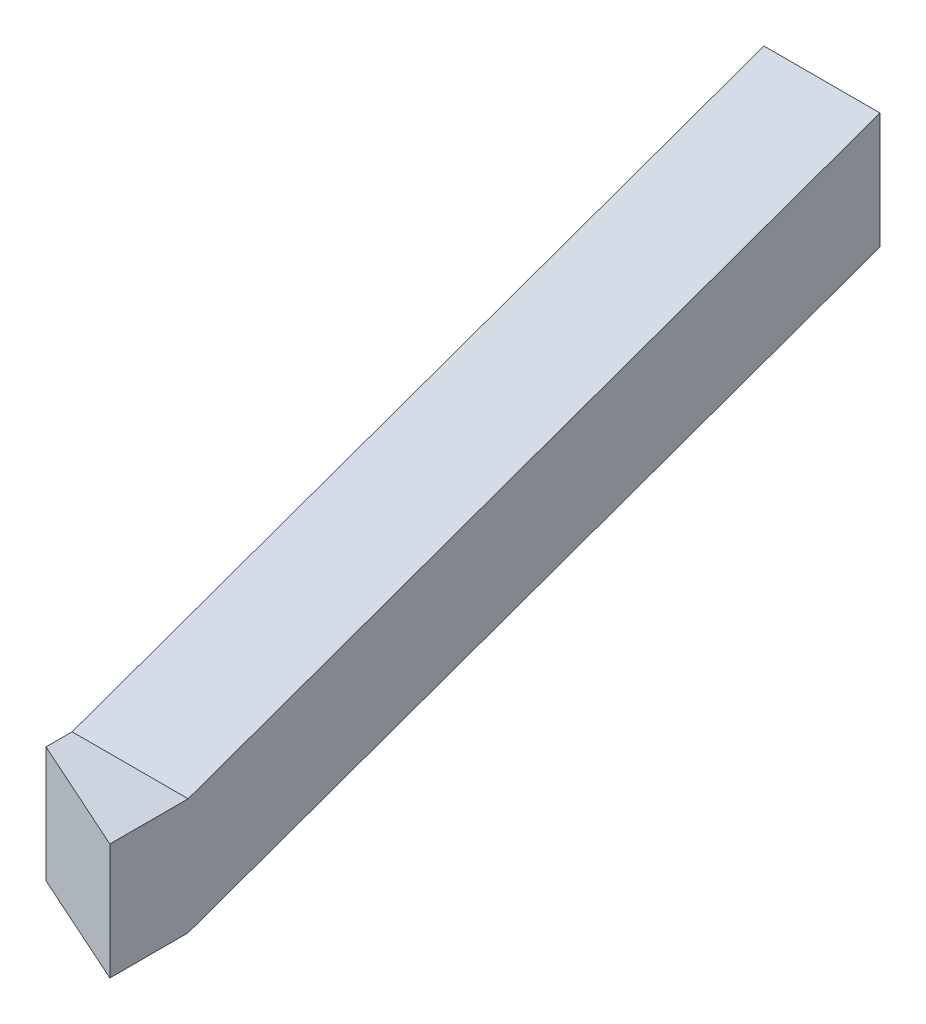
SolidWorks part; units mm, degrees
ref_plane "Alzado" through (0, 0, 0) normal (0, 0, 1) x (1, 0, 0)
ref_plane "Planta" through (0, 0, 0) normal (0, 1, 0) x (1, 0, 0)
ref_plane "Vista lateral" through (0, 0, 0) normal (1, 0, 0) x (0, 0, -1)
sketch "Croquis1" plane through (0, 0, 0) normal (0, 0, 1) x (1, 0, 0)
  line L1 (0, 0) -> (88.9, 0)
  line L2 (0, 0) -> (0, 88.9)
  line L3 (0, 88.9) -> (88.9, 88.9)
  line L4 (88.9, 0) -> (88.9, 88.9)
  dimension "D1" = 88.9
  dimension "D2" = 88.9
extrude "Saliente-Extruir1" add sketch "Croquis1" against normal blind 60
sketch3d "Croquis3D1"
  line L0 (44.45, 88.9, -60) -> (44.45, 0, -60) construction
  line L1 (88.9, 88.9, -60) -> (0, 88.9, -60) construction
  line L2 (0, 0, -60) -> (88.9, 0, -60) construction
  line L3 (44.45, 44.45, -60) -> (44.45, 44.45, -590) construction
  line L4 (44.45, 44.45, -590) -> (44.45, 234.45, -590) construction
  line L5 (44.45, 234.45, -590) -> (44.45, 44.45, -60)
  dimension "D1" = 530
  dimension "D2" = 190
sketch "Croquis2" plane through (0, 0, -60) normal (0, 0, -1) x (-1, 0, 0)
  line L1 (-88.9, 88.9) -> (0, 88.9)
  line L2 (-88.9, 88.9) -> (-88.9, 0)
  line L3 (-88.9, 0) -> (0, 0)
  line L4 (0, 88.9) -> (0, 0)
sweep "Barrer1" add profiles "Croquis2" path "Croquis3D1"
sketch "Croquis3" plane through (0, 88.9, 0) normal (0, 1, 0) x (1, 0, 0)
  line L0 (88.9, 0) -> (0, 40)
  line L2 (0, 60) -> (0, 0) construction
  line L3 (0, 40) -> (0, 0)
  line L4 (0, 0) -> (88.9, 0)
  dimension "D1" = 40
extrude "Cortar-Extruir1" cut sketch "Croquis3" against normal blind 100
